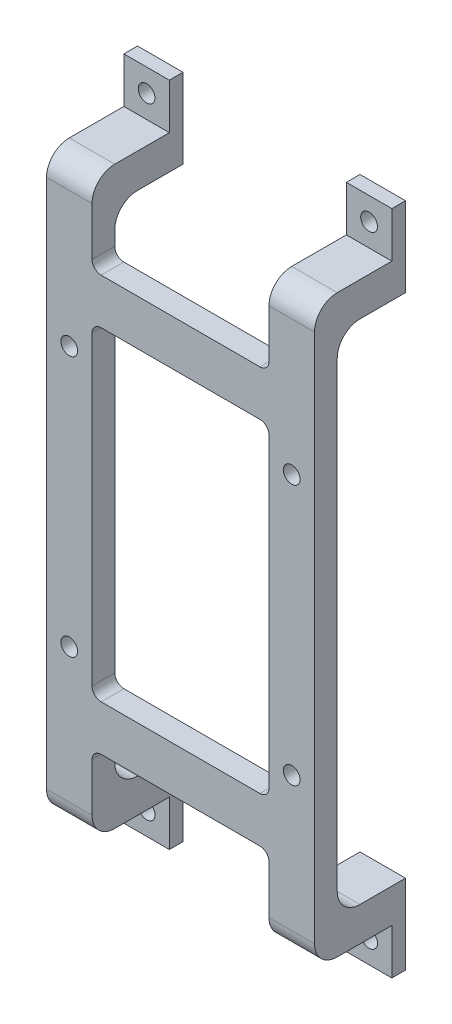
SolidWorks part; units mm, degrees
ref_plane "Plan de face" through (0, 0, 0) normal (0, 0, 1) x (1, 0, 0)
ref_plane "Plan de dessus" through (0, 0, 0) normal (0, 1, 0) x (1, 0, 0)
ref_plane "Plan de droite" through (0, 0, 0) normal (1, 0, 0) x (0, 0, -1)
sketch "Esquisse1" plane through (0, 0, 0) normal (0, 0, 1) x (1, 0, 0)
  line L0 (-29.45, 73.225) -> (-19.45, 73.225)
  line L1 (-19.45, 73.225) -> (-19.45, -73.225)
  line L2 (-19.45, -73.225) -> (-29.45, -73.225)
  line L3 (-29.45, -73.225) -> (-29.45, 73.225)
  dimension "D1" = 10
  dimension "D2" = 146.45
  dimension "D3" = 73.225
  dimension "D4" = 29.45
extrude "Boss.-Extru.3" add sketch "Esquisse1" along normal blind 3 contours L3 L0 L1 L2
sketch "Esquisse3" plane through (0, 0, 3) normal (0, 0, 1) x (1, 0, 0)
  line L0 (-29.45, -63.225) -> (-19.45, -63.225)
  line L1 (-29.45, -73.225) -> (-29.45, 73.225) construction
  line L2 (-19.45, 73.225) -> (-19.45, -73.225) construction
  line L3 (-19.45, -63.225) -> (-19.45, 63.225)
  line L4 (-19.45, 63.225) -> (-29.45, 63.225)
  line L5 (-29.45, 63.225) -> (-29.45, -63.225)
  line L6 (-19.45, -73.225) -> (-29.45, -73.225) construction
  line L7 (-29.45, 73.225) -> (-19.45, 73.225) construction
  dimension "D1" = 10
  dimension "D2" = 10
extrude "Boss.-Extru.4" add sketch "Esquisse3" along normal blind 17
sketch "Esquisse4" plane through (0, 0, 3) normal (0, 0, 1) x (1, 0, 0)
  line L0 (-19.45, -63.225) -> (-19.45, -73.225) construction
  line L2 (-19.45, -73.225) -> (-29.45, -73.225) construction
  circle A0 centre (-24.45, -68.225) radius 1.84
  point P4 (0, 0)
  point P6 (-25.4912, -73.225)
  dimension "D1" = 5
  dimension "D2" = 5
extrude "Enlèv. mat.-Extru.1" cut sketch "Esquisse4" against normal blind 17 contours A0
mirror "Symétrie1" about plane through (0, 0, 0) normal (0, 1, 0) of "Enlèv. mat.-Extru.1"
sketch "Esquisse5" plane through (0, 0, 20) normal (0, 0, 1) x (1, 0, 0)
  line L0 (-19.45, -63.225) -> (-19.45, 63.225) construction
  line L1 (-29.45, 73.225) -> (-19.45, 73.225) construction
  circle A0 centre (-24.45, 28.61) radius 1.84
  dimension "D1" = 5
  dimension "D2" = 44.615
extrude "Enlèv. mat.-Extru.2" cut sketch "Esquisse5" against normal through all
mirror "Symétrie2" about plane through (0, 0, 0) normal (0, 1, 0) of "Enlèv. mat.-Extru.2"
sketch "Esquisse6" plane through (-29.45, 0, 0) normal (-1, 0, 0) x (0, 0, 1)
  line L0 (0, 55.725) -> (15, 55.725)
  line L2 (0, -73.225) -> (0, 73.225) construction
  line L3 (15, 55.725) -> (15, -55.725)
  line L4 (15, -55.725) -> (0, -55.725)
  line L5 (0, -55.725) -> (0, 55.725)
  line L6 (20, 63.225) -> (3, 63.225) construction
  line L7 (20, -63.225) -> (3, -63.225) construction
  line L8 (20, 63.225) -> (20, -63.225) construction
  dimension "D1" = 7.5
  dimension "D2" = 7.5
  dimension "D3" = 5
extrude "Enlèv. mat.-Extru.3" cut sketch "Esquisse6" against normal through all
fillet "Congé1" radius 5 2 edges at (-24.45, -63.225, 20) (-24.45, 63.225, 20)
fillet "Congé2" radius 5 2 edges at (-24.45, -55.725, 15) (-24.45, 55.725, 15)
pattern_linear "Répétition linéaire1" count 2 spacing 48.9 along (1, 0, 0) of bodies 109
sketch "Esquisse7" plane through (0, 0, 15) normal (0, 0, -1) x (-1, 0, 0)
  line L0 (-29.45, 45.606) -> (-29.45, 35.606)
  line L1 (-29.45, -50.725) -> (-29.45, 50.725) construction
  line L2 (-29.45, 35.606) -> (29.45, 35.606)
  line L3 (29.45, -50.725) -> (29.45, 50.725) construction
  line L4 (29.45, 35.606) -> (29.45, 45.606)
  line L5 (29.45, 45.606) -> (-29.45, 45.606)
  dimension "D1" = 10
  dimension "D2" = 58.9
extrude "Boss.-Extru.5" add sketch "Esquisse7" against normal blind 5
fillet "Congé4" radius 2 4 edges at (-19.45, 45.606, 17.5) (-19.45, 35.606, 17.5) (19.45, 35.606, 17.5) (19.45, 45.606, 17.5)
sketch "Esquisse8" plane through (0, 0, 15) normal (0, 0, -1) x (-1, 0, 0)
  line L0 (-29.45, -35.605) -> (-29.45, -45.605)
  line L1 (-29.45, 50.725) -> (-29.45, -50.725) construction
  line L2 (-29.45, -45.605) -> (29.45, -45.605)
  line L3 (29.45, -50.725) -> (29.45, 50.725) construction
  line L4 (29.45, -45.605) -> (29.45, -35.605)
  line L5 (29.45, -35.605) -> (-29.45, -35.605)
  line L6 (19.45, -73.225) -> (29.45, -73.225) construction
  dimension "D1" = 10
  dimension "D2" = 27.62
extrude "Boss.-Extru.6" add sketch "Esquisse8" against normal blind 5
fillet "Congé5" radius 2 4 edges at (19.45, -45.605, 17.5) (19.45, -35.605, 17.5) (-19.45, -35.605, 17.5) (-19.45, -45.605, 17.5)
